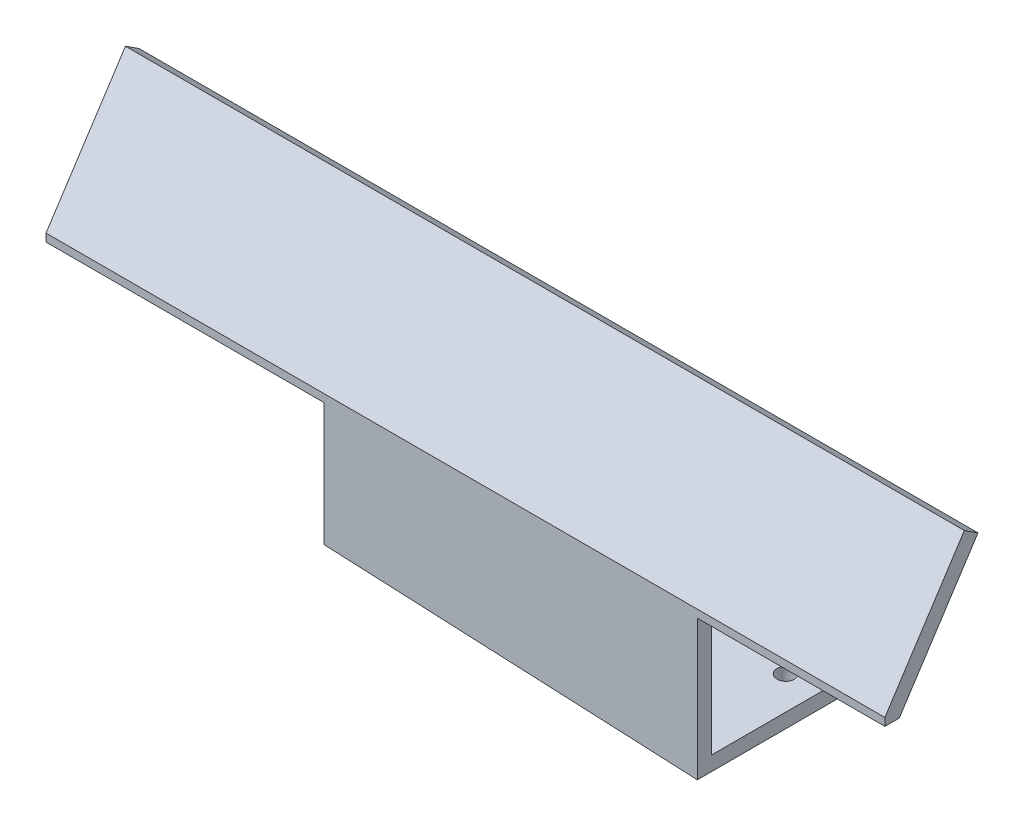
SolidWorks part; units mm, degrees
ref_plane "Front Plane" through (0, 0, 0) normal (0, 0, 1) x (1, 0, 0)
ref_plane "Top Plane" through (0, 0, 0) normal (0, 1, 0) x (1, 0, 0)
ref_plane "Right Plane" through (0, 0, 0) normal (1, 0, 0) x (0, 0, -1)
sketch "Sketch1" plane through (0, 0, 0) normal (1, 0, 0) x (0, 0, -1)
  line L0 (-8.5882, -21.7096) -> (-8.5882, -3.2096)
  line L1 (7.9896, 22.2725) -> (10.8396, 20.4184)
  line L2 (-8.5882, -3.2096) -> (7.9896, 22.2725)
  line L3 (10.8396, 20.4184) -> (-5.5882, -4.8331)
  line L4 (-5.5882, -21.7096) -> (-5.5882, -4.8331)
  line L5 (-8.5882, -21.7096) -> (-5.5882, -21.7096)
extrude "Boss-Extrude1" add sketch "Sketch1" along normal blind 175
sketch "Sketch2" plane through (0, 0, 5.5882) normal (0, 0, -1) x (-1, 0, 0)
  line L0 (-175, -4.8331) -> (-175, -35.8331)
  line L1 (-175, -4.8331) -> (0, -4.8331)
  line L2 (0, -4.8331) -> (0, -27.8331)
  line L3 (0, -27.8331) -> (-175, -35.8331)
extrude "Boss-Extrude2" add sketch "Sketch2" against normal blind 3
sketch "Sketch3" plane through (-1.2697, -27.775, 0) normal (-0.0457, -0.999, 0) x (0.999, -0.0457, 0)
  line L1 (1.271, 8.5882) -> (176.4538, 8.5882)
  line L2 (1.271, 8.5882) -> (1.271, -21.4118)
  line L3 (1.271, -21.4118) -> (176.4538, -21.4118)
  line L4 (176.4538, 8.5882) -> (176.4538, -21.4118)
extrude "Boss-Extrude3" add sketch "Sketch3" against normal blind 3
sketch "Sketch5" plane through (0, 0, 5.5882) normal (0, 0, -1) x (-1, 0, 0)
  line L4 (-153, -4.8331) -> (-153, -39.9058)
  line L5 (0, -4.8331) -> (-58, -4.8331)
  line L6 (0, -4.8331) -> (0, -41.4738)
  line L7 (0, -41.4738) -> (-58, -41.4738)
  line L8 (-58, -4.8331) -> (-58, -41.4738)
  line L10 (-153, -4.8331) -> (-153, -39.9058)
  line L13 (-153, -4.8331) -> (-195.3706, -4.8331)
  line L14 (-153, -4.8331) -> (-153, -39.9058)
  line L15 (-153, -39.9058) -> (-195.3706, -39.9058)
  line L16 (-195.3706, -4.8331) -> (-195.3706, -39.9058)
  line M2 (-175, -32.83) -> (-0.137, -24.8362)
  line M3 (-0.137, -24.8362) -> (0, -27.8331)
  line M4 (0, -27.8331) -> (0, -4.8331)
  line M5 (0, -4.8331) -> (-175, -4.8331)
  line M6 (-175, -4.8331) -> (-175, -32.83)
extrude "Cut-Extrude2" cut sketch "Sketch5" against normal through all both and the other way through all contours L4 M5 M6 M2 | L13 L16 L15 L4 M2 M6 | L8 L7 L6 M2 M3 | L8 M5 M2 M3 M4
sketch "Sketch6" plane through (-1.1327, -24.7782, 0) normal (0.0457, 0.999, 0) x (0.999, -0.0457, 0)
  line L0 (154.2937, 21.4118) -> (154.2937, -5.5882) construction
  line L1 (59.1945, 21.4118) -> (154.2937, 21.4118)
  line L2 (59.1945, 21.4118) -> (59.1945, 16.4118)
  line L4 (154.2937, 21.4118) -> (154.2937, 16.4118)
  line L5 (106.7441, 16.4118) -> (106.7441, 21.4118)
  line L6 (106.7441, 16.4118) -> (59.1945, 16.4118)
  circle A0 centre (82.9693, 16.4118) radius 1.8
  circle A1 centre (130.5189, 16.4118) radius 1.8
extrude "Cut-Extrude3" cut sketch "Sketch6" against normal through all both contours A0 | A1
sketch "Sketch7" plane through (0, 0, 5.5882) normal (0, 0, -1) x (-1, 0, 0)
  line L1 (-153, -4.8331) -> (-135.8763, -4.8331)
  line L2 (-153, -4.8331) -> (-153, -42.119)
  line L3 (-153, -42.119) -> (-135.8763, -42.119)
  line L4 (-135.8763, -4.8331) -> (-135.8763, -42.119)
extrude "Cut-Extrude4" cut sketch "Sketch7" against normal through all both and the other way through all
